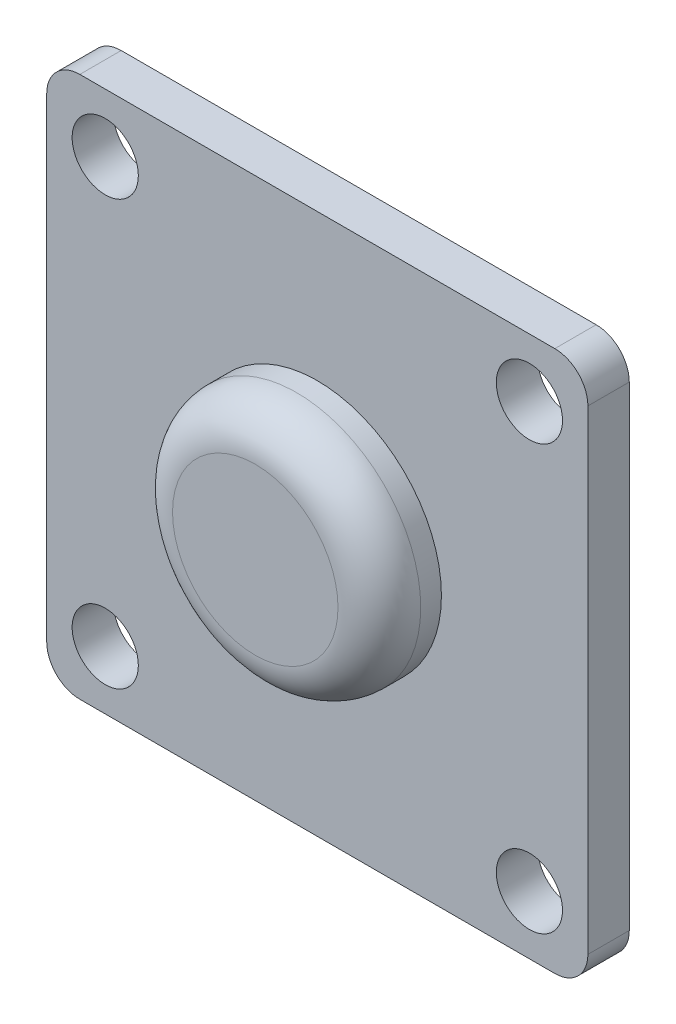
SolidWorks part; units mm, degrees
ref_plane "前视基准面" through (0, 0, 0) normal (0, 0, 1) x (1, 0, 0)
ref_plane "上视基准面" through (0, 0, 0) normal (0, 1, 0) x (1, 0, 0)
ref_plane "右视基准面" through (0, 0, 0) normal (1, 0, 0) x (0, 0, -1)
sketch "草图1" plane through (0, 0, 0) normal (0, 0, 1) x (1, 0, 0)
  line L1 (-13.0815, -13.0815) -> (13.0815, -13.0815)
  line L2 (-13.0815, -13.0815) -> (-13.0815, 13.0815)
  line L3 (-13.0815, 13.0815) -> (13.0815, 13.0815)
  line L4 (13.0815, -13.0815) -> (13.0815, 13.0815)
  line L5 (-13.0815, -13.0815) -> (13.0815, 13.0815) construction
  line L6 (-13.0815, 13.0815) -> (13.0815, -13.0815) construction
  line L11 (-10.253, -10.253) -> (10.253, 10.253) construction
  line L12 (-10.253, 10.253) -> (10.253, -10.253) construction
  circle A0 centre (10.253, 10.253) radius 1.6
  circle A1 centre (-10.253, 10.253) radius 1.6
  circle A2 centre (-10.253, -10.253) radius 1.6
  circle A3 centre (10.253, -10.253) radius 1.6
  point P0 (0, 0)
  point P6 (0, 0)
extrude "凸台-拉伸1" add sketch "草图1" along normal blind 2
sketch "草图2" plane through (0, 0, 2) normal (0, 0, 1) x (1, 0, 0)
  circle A0 centre (0, 0) radius 6
extrude "凸台-拉伸2" add sketch "草图2" along normal blind 3
sketch "草图3" plane through (0, 0, 0) normal (0, 0, -1) x (-1, 0, 0)
  circle A0 centre (0, 0) radius 3.1
extrude "切除-拉伸1" cut sketch "草图3" against normal blind 3
fillet "圆角2" radius 2 1 edges at (6, 0, 5)
fillet "圆角3" radius 1.6 4 edges at (-13.0815, 13.0815, 1) (13.0815, 13.0815, 1) (13.0815, -13.0815, 1) (-13.0815, -13.0815, 1)
